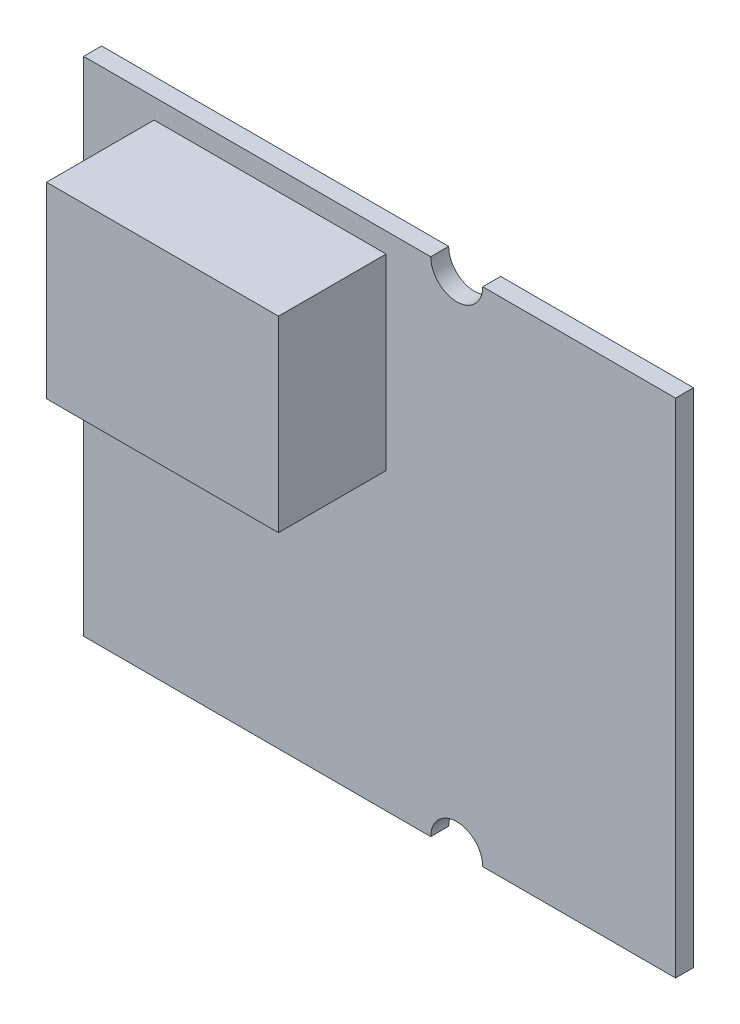
SolidWorks part; units mm, degrees
ref_plane "Спереди" through (0, 0, 0) normal (0, 0, 1) x (1, 0, 0)
ref_plane "Сверху" through (0, 0, 0) normal (0, 1, 0) x (1, 0, 0)
ref_plane "Справа" through (0, 0, 0) normal (1, 0, 0) x (0, 0, -1)
sketch "Эскиз1" plane through (0, 0, 0) normal (0, 0, 1) x (1, 0, 0)
  line L0 (0, 25.8016) -> (0, 57.6785) construction
  line L1 (0, 0) -> (19.35, 0)
  line L2 (0, 0) -> (0, 12.55)
  line L3 (0, 28) -> (19.35, 28)
  line L4 (33, 0) -> (33, 28)
  line L5 (20.8, 28) -> (20.8, 55.8717) construction
  line L6 (22.25, 28) -> (33, 28)
  line L7 (20.8, 28) -> (20.8, 50028) construction
  line L8 (22.25, 0) -> (33, 0)
  line L9 (0, 14) -> (33, 14) construction
  line L10 (0, 15.45) -> (0, 28)
  arc A0 (19.35, 28) -> (22.25, 28) centre (20.8, 28) ccw
  arc A1 (22.25, 0) -> (19.35, 0) centre (20.8, 0) ccw
  arc A2 (0, 12.55) -> (0, 15.45) centre (0, 14) ccw
  dimension "D4" = 2.9
  dimension "D5" = 2.9
  dimension "D6" = 2.9
  dimension "D1" = 33
  dimension "D2" = 28
  dimension "D3" = 20.8
extrude "Бобышка-Вытянуть1" add sketch "Эскиз1" along normal blind 1
sketch "Эскиз2" plane through (0, 0, 1) normal (0, 0, 1) x (1, 0, 0)
  line L1 (3.9278, 26.8876) -> (16.8633, 26.8876)
  line L2 (3.9278, 26.8876) -> (3.9278, 16.4329)
  line L3 (3.9278, 16.4329) -> (16.8633, 16.4329)
  line L4 (16.8633, 26.8876) -> (16.8633, 16.4329)
  point P4 (16.8633, 16.4329)
extrude "Бобышка-Вытянуть2" add sketch "Эскиз2" along normal blind 6
